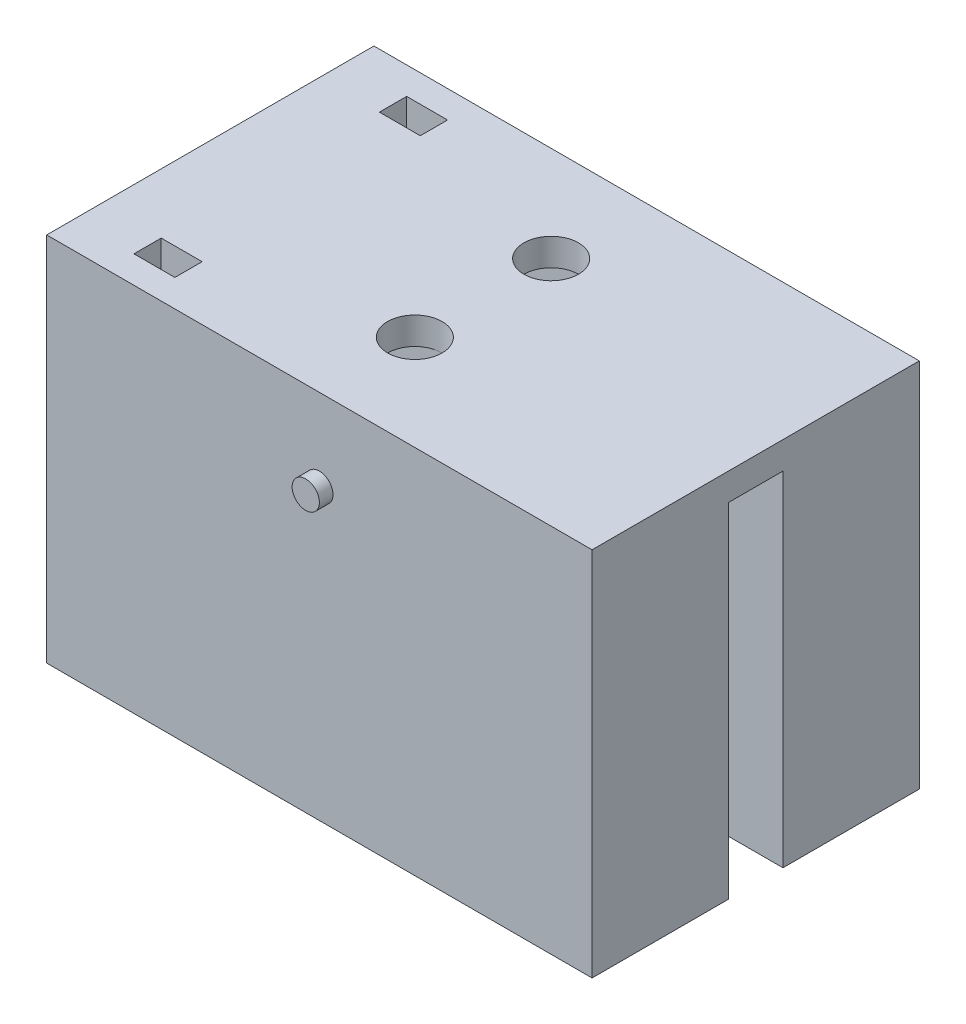
SolidWorks part; units mm, degrees
ref_plane "前视基准面" through (0, 0, 0) normal (0, 0, 1) x (1, 0, 0)
ref_plane "上视基准面" through (0, 0, 0) normal (0, 1, 0) x (1, 0, 0)
ref_plane "右视基准面" through (0, 0, 0) normal (1, 0, 0) x (0, 0, -1)
sketch "草图1" plane through (0, 0, 0) normal (0, 1, 0) x (1, 0, 0)
  line L0 (0, 0) -> (11.2311, 0) construction
  line L1 (-100, 60) -> (100, 60)
  line L2 (-100, 60) -> (-100, -60)
  line L3 (-100, -60) -> (100, -60)
  line L4 (100, 60) -> (100, -60)
  line L5 (-100, 60) -> (100, -60) construction
  line L6 (-100, -60) -> (100, 60) construction
  line L7 (-63, 40) -> (-63, 50)
  line L8 (-78, -40) -> (-63, -40)
  line L9 (-78, -40) -> (-78, -50)
  line L10 (-78, -50) -> (-63, -50)
  line L11 (-63, -40) -> (-63, -50)
  line L12 (-78, -40) -> (-63, -50) construction
  line L13 (-78, -50) -> (-63, -40) construction
  line L14 (-78, 50) -> (-63, 50)
  line L15 (-78, 40) -> (-78, 50)
  line L16 (-78, 40) -> (-63, 40)
  circle A0 centre (0, 25) radius 10
  circle A1 centre (0, -25) radius 10
  point P0 (0, 0)
  point P12 (-70.5, -45)
  dimension "D3" = 20
  dimension "D1" = 200
  dimension "D2" = 120
  dimension "D4" = 50
  dimension "D5" = 15
  dimension "D6" = 10
  dimension "D7" = 22
  dimension "D8" = 10
extrude "凸台-拉伸1" add sketch "草图1" along normal blind 10
sketch "草图2" plane through (0, 0, 0) normal (0, -1, 0) x (1, 0, 0)
  line L1 (-100, 60) -> (100, 60)
  line L2 (-100, 60) -> (-100, -60)
  line L3 (-100, -60) -> (100, -60)
  line L4 (100, 60) -> (100, -60)
  line L5 (-100, 60) -> (100, -60) construction
  line L6 (-100, -60) -> (100, 60) construction
  line L7 (-90, 50) -> (90, 50)
  line L8 (-90, 50) -> (-90, -50)
  line L9 (-90, -50) -> (90, -50)
  line L10 (90, 50) -> (90, -50)
  line L11 (-90, 50) -> (90, -50) construction
  line L12 (-90, -50) -> (90, 50) construction
  point P0 (0, 0)
  point P7 (0, 0)
  dimension "D1" = 180
  dimension "D2" = 100
extrude "凸台-拉伸2" add sketch "草图2" along normal blind 116
sketch "草图4" plane through (0, -116, 0) normal (0, -1, 0) x (1, 0, 0)
  line L1 (-100, 60) -> (100, 60)
  line L2 (-100, 60) -> (-100, -60)
  line L3 (-100, -60) -> (100, -60)
  line L4 (100, 60) -> (100, -60)
  line L5 (-100, 60) -> (100, -60) construction
  line L6 (-100, -60) -> (100, 60) construction
  point P0 (0, 0)
extrude "凸台-拉伸3" add sketch "草图4" along normal blind 10
sketch "草图6" plane through (0, -126, 0) normal (0, -1, 0) x (1, 0, 0)
  line L0 (100, -60) -> (100, 60) construction
  line L1 (-100, 10) -> (100, 10)
  line L2 (-100, 10) -> (-100, -10)
  line L3 (-100, -10) -> (100, -10)
  line L4 (100, 10) -> (100, -10)
  line L5 (-100, 10) -> (100, -10) construction
  line L6 (-100, -10) -> (100, 10) construction
  point P0 (0, 0)
  dimension "D1" = 20
extrude "切除-拉伸1" cut sketch "草图6" against normal blind 126
sketch "草图7" plane through (0, 0, 10) normal (0, 0, -1) x (-1, 0, 0)
  line L0 (-100, 10) -> (-100, -126) construction
  line L1 (-100, 0) -> (100, 0)
  line L2 (-100, 0) -> (-100, -126)
  line L3 (-100, -126) -> (100, -126)
  line L4 (100, 0) -> (100, -126)
extrude "凸台-拉伸4" add sketch "草图7" against normal blind 5
sketch "草图8" plane through (0, 0, -10) normal (0, 0, 1) x (1, 0, 0)
  line L0 (-100, 10) -> (-100, -126) construction
  line L1 (-100, 0) -> (100, 0)
  line L2 (-100, 0) -> (-100, -126)
  line L3 (-100, -126) -> (100, -126)
  line L4 (100, 0) -> (100, -126)
extrude "凸台-拉伸5" add sketch "草图8" against normal blind 5
sketch "草图9" plane through (0, 0, -10) normal (0, 0, 1) x (1, 0, 0)
  line L0 (-100, 0) -> (100, 0) construction
  circle A0 centre (0, -20) radius 8
  dimension "D1" = 16
  dimension "D2" = 20
extrude "凸台-拉伸6" add sketch "草图9" along normal blind 20
sketch "草图10" plane through (0, 0, 60) normal (0, 0, 1) x (1, 0, 0)
  line L0 (-100, 10) -> (100, 10) construction
  circle A0 centre (0, -20) radius 5
  dimension "D1" = 30
  dimension "D2" = 10
extrude "凸台-拉伸7" add sketch "草图10" along normal blind 5
sketch "草图11" plane through (0, 0, -60) normal (0, 0, -1) x (-1, 0, 0)
  line L0 (-100, 10) -> (100, 10) construction
  circle A0 centre (0, -20) radius 5
  dimension "D1" = 30
extrude "凸台-拉伸8" add sketch "草图11" along normal blind 5
